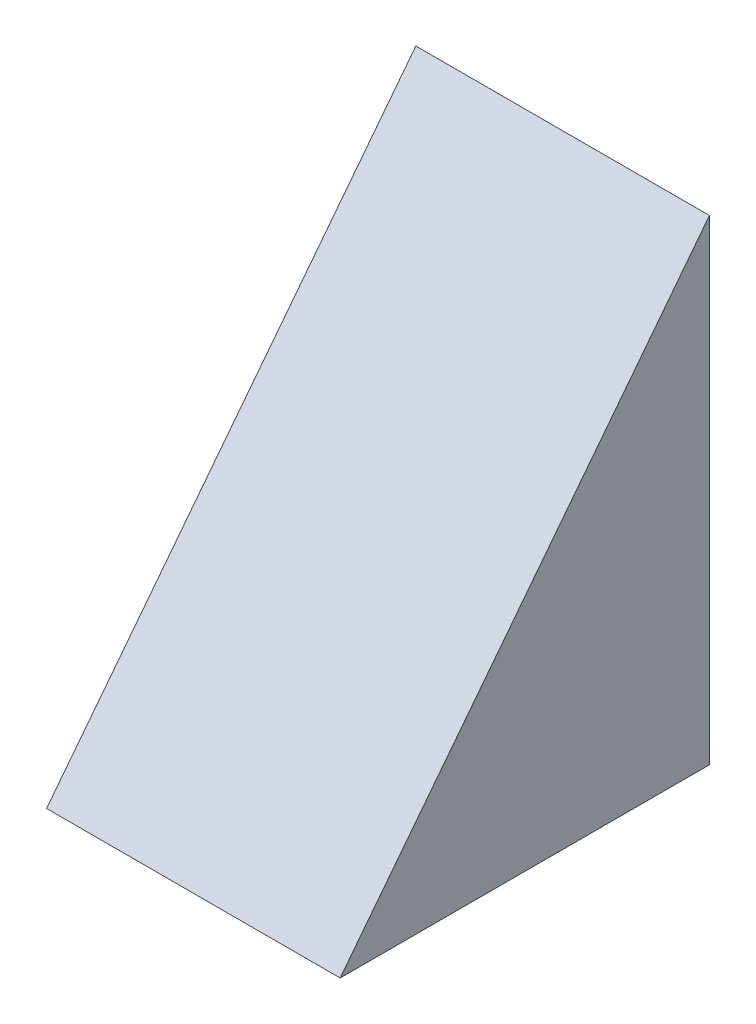
SolidWorks part; units mm, degrees
ref_plane "Front Plane" through (0, 0, 0) normal (0, 0, 1) x (1, 0, 0)
ref_plane "Top Plane" through (0, 0, 0) normal (0, 1, 0) x (1, 0, 0)
ref_plane "Right Plane" through (0, 0, 0) normal (1, 0, 0) x (0, 0, -1)
sketch "Sketch1" plane through (0, 0, 0) normal (0, 0, 1) x (1, 0, 0)
  line L1 (-195, 315.976) -> (0, 315.976)
  line L2 (-195, 315.976) -> (-195, 0)
  line L3 (-195, 0) -> (0, 0)
  line L4 (0, 315.976) -> (0, 0)
  dimension "D1" = 195
  dimension "D2" = 315.976
extrude "Boss-Extrude2" add sketch "Sketch1" along normal blind 257.302
sketch "Sketch3" plane through (0, 0, 0) normal (1, 0, 0) x (0, 0, -1)
  line L0 (0, 315.976) -> (-245.2737, 0)
  line L1 (-257.302, 0) -> (0, 0) construction
  point P5 (0, 0)
  point P6 (0, 0)
  dimension "D1" = 400
extrude "Cut-Extrude1" cut sketch "Sketch3" against normal blind 195 and the other way through all flip side to cut
